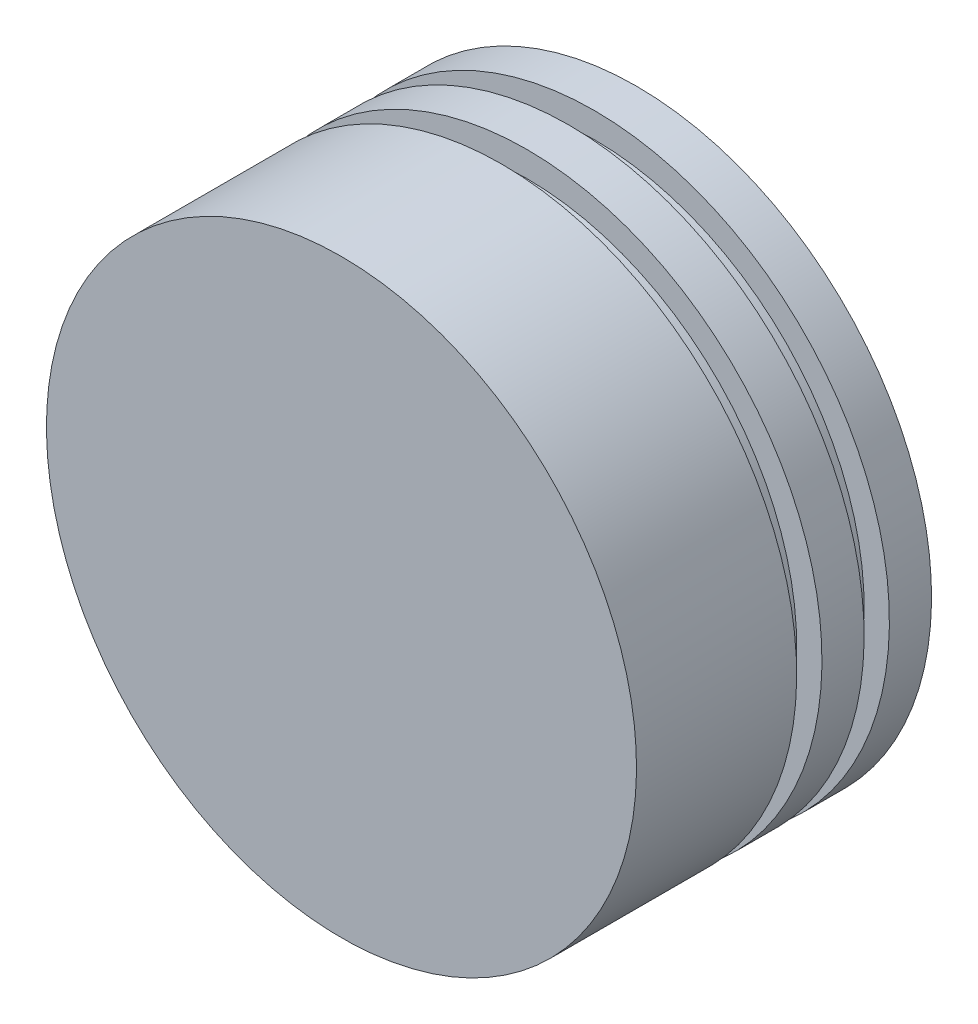
SolidWorks part; units mm, degrees
ref_plane "Front Plane" through (0, 0, 0) normal (0, 0, 1) x (1, 0, 0)
ref_plane "Top Plane" through (0, 0, 0) normal (0, 1, 0) x (1, 0, 0)
ref_plane "Right Plane" through (0, 0, 0) normal (1, 0, 0) x (0, 0, -1)
sketch "Sketch1" plane through (0, 0, 0) normal (1, 0, 0) x (0, 0, -1)
  line L0 (0, 0) -> (0, -10)
  line L1 (0, -10) -> (19, -10)
  line L3 (30, -10) -> (35, -10)
  line L4 (35, -10) -> (35, 25)
  line L7 (35, 25) -> (15, 25)
  line L8 (15, 25) -> (15, 0)
  line L9 (15, 0) -> (0, 0)
  line L10 (30, -10) -> (30, -7)
  line L11 (30, -7) -> (27, -7)
  line L12 (27, -7) -> (27, -10)
  line L13 (27, -10) -> (22, -10)
  line L14 (22, -10) -> (22, -7)
  line L15 (22, -7) -> (19, -7)
  line L16 (19, -7) -> (19, -10)
  dimension "D6" = 3
  dimension "D7" = 5
  dimension "D1" = 35
  dimension "D2" = 10
  dimension "D3" = 3
  dimension "D4" = 5
  dimension "D5" = 15
  dimension "D8" = 3
  dimension "D9" = 35
revolve "Revolve1" add sketch "Sketch1" angle 360 about L7
sketch "Sketch2" [suppressed] plane through (0, 0, 0) normal (0, 1, 0) x (1, 0, 0)
  circle A0 centre (0, 8) radius 3
  dimension "D1" = 6
  dimension "D2" = 8
  dimension "D3" = 0
extrude "Cut-Extrude3" [suppressed] cut sketch "Sketch2" against normal mid plane 25
pattern_circular "CirPattern1" [suppressed] count 8 over 360
sketch "Sketch4" plane through (0, 0, 0) normal (0, 0, 1) x (1, 0, 0)
  circle A0 centre (0, 25) radius 25
extrude "Boss-Extrude4" add sketch "Sketch4" against normal up to next
sketch "Sketch5" plane through (0, 0, -35) normal (0, 0, -1) x (-1, 0, 0)
  circle A0 centre (0, 25) radius 24
  dimension "D1" = 48
extrude "Cut-Extrude5" cut sketch "Sketch5" against normal blind 15 contours A0
